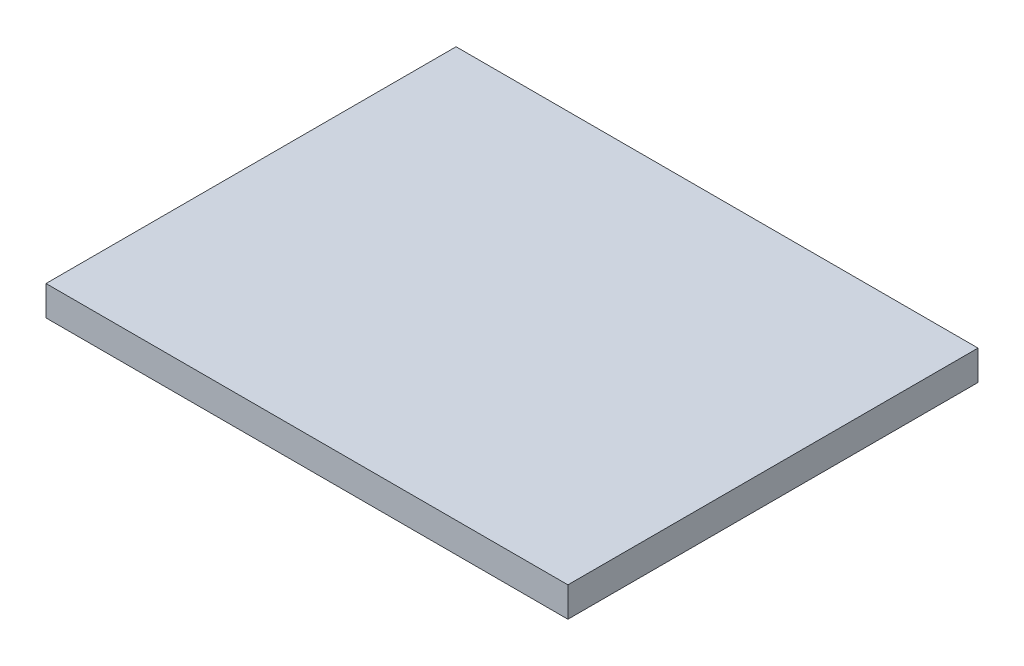
SolidWorks part; units mm, degrees
ref_plane "Front Plane" through (0, 0, 0) normal (0, 0, 1) x (1, 0, 0)
ref_plane "Top Plane" through (0, 0, 0) normal (0, 1, 0) x (1, 0, 0)
ref_plane "Right Plane" through (0, 0, 0) normal (1, 0, 0) x (0, 0, -1)
sketch "Sketch1" plane through (0, 0, 0) normal (0, 1, 0) x (1, 0, 0)
  line L1 (-35, 27.5) -> (35, 27.5)
  line L2 (-35, 27.5) -> (-35, -27.5)
  line L3 (-35, -27.5) -> (35, -27.5)
  line L4 (35, 27.5) -> (35, -27.5)
  line L5 (-35, 27.5) -> (35, -27.5) construction
  line L6 (-35, -27.5) -> (35, 27.5) construction
  point P0 (0, 0)
  dimension "D1" = 55
  dimension "D2" = 70
extrude "Boss-Extrude1" add sketch "Sketch1" along normal blind 4
